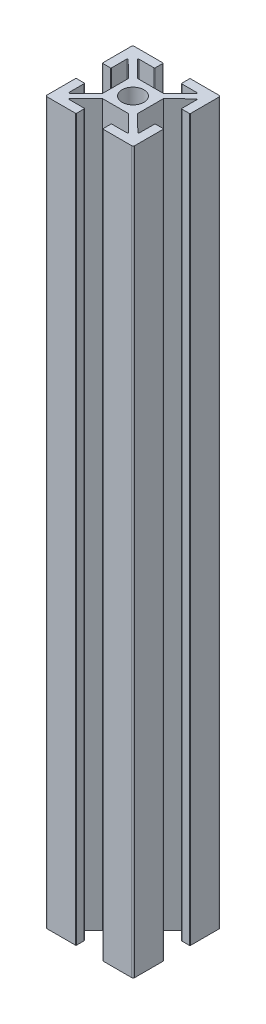
SolidWorks part; units mm, degrees
ref_plane "Front Plane" through (0, 0, 0) normal (0, 0, 1) x (1, 0, 0)
ref_plane "Top Plane" through (0, 0, 0) normal (0, 1, 0) x (1, 0, 0)
ref_plane "Right Plane" through (0, 0, 0) normal (1, 0, 0) x (0, 0, -1)
sketch "Sketch1" plane through (0, 0, 0) normal (0, 1, 0) x (1, 0, 0)
  line L0 (-9.8963, 3) -> (-8.1963, 3)
  line L3 (-3.1963, 10) -> (-9.6963, 10)
  line L4 (-10.0463, 3.15) -> (-10.0463, 9.65)
  line L7 (2.9332, 4) -> (-2.9332, 4)
  line L8 (-4, -2.9454) -> (-4, 2.9454)
  line L9 (-8.0463, 3.15) -> (-8.0463, 6.5862)
  line L10 (-6.6144, 8) -> (-3.1963, 8)
  line L11 (-3.0463, 8.15) -> (-3.0463, 9.85)
  line L12 (-8.0463, 8) -> (-4, 4) construction
  line L13 (-7.7908, 6.6929) -> (-4, 2.9454)
  line L14 (-6.7198, 7.7433) -> (-2.9332, 4)
  line L15 (8.0463, 8) -> (4, 4) construction
  line L22 (0, 0) -> (0, 11.6886) construction
  line L25 (0, 0) -> (-14.9841, 0) construction
  line L27 (6.7198, 7.7433) -> (2.9332, 4)
  line L28 (7.7908, 6.6929) -> (4, 2.9454)
  line L46 (3.0463, 8.15) -> (3.0463, 9.85)
  line L47 (6.6144, 8) -> (3.1963, 8)
  line L48 (8.0463, 3.15) -> (8.0463, 6.5862)
  line L49 (4, -2.9454) -> (4, 2.9454)
  line L50 (10.0463, 3.15) -> (10.0463, 9.65)
  line L51 (3.1963, 10) -> (9.6963, 10)
  line L52 (9.8963, 3) -> (8.1963, 3)
  line L53 (8.0463, -8) -> (4, -4) construction
  line L54 (-8.0463, -8) -> (-4, -4) construction
  line L55 (9.8963, -3) -> (8.1963, -3)
  line L56 (3.1963, -10) -> (9.6963, -10)
  line L57 (10.0463, -3.15) -> (10.0463, -9.65)
  line L58 (8.0463, -3.15) -> (8.0463, -6.5862)
  line L59 (6.6144, -8) -> (3.1963, -8)
  line L60 (3.0463, -8.15) -> (3.0463, -9.85)
  line L61 (7.7908, -6.6929) -> (4, -2.9454)
  line L62 (6.7198, -7.7433) -> (2.9332, -4)
  line L63 (-6.7198, -7.7433) -> (-2.9332, -4)
  line L64 (-7.7908, -6.6929) -> (-4, -2.9454)
  line L65 (-3.0463, -8.15) -> (-3.0463, -9.85)
  line L66 (-6.6144, -8) -> (-3.1963, -8)
  line L67 (-8.0463, -3.15) -> (-8.0463, -6.5862)
  line L68 (2.9332, -4) -> (-2.9332, -4)
  line L69 (-10.0463, -3.15) -> (-10.0463, -9.65)
  line L70 (-3.1963, -10) -> (-9.6963, -10)
  line L71 (-9.8963, -3) -> (-8.1963, -3)
  circle A0 centre (0, 0) radius 2.5
  arc A1 (-10.0463, 9.65) -> (-9.6963, 10) centre (-9.6963, 9.65) cw
  arc A2 (-9.8963, 3) -> (-10.0463, 3.15) centre (-9.8963, 3.15) cw
  arc A3 (-8.1963, 3) -> (-8.0463, 3.15) centre (-8.1963, 3.15) ccw
  arc A4 (-3.1963, 10) -> (-3.0463, 9.85) centre (-3.1963, 9.85) cw
  arc A5 (-3.1963, 8) -> (-3.0463, 8.15) centre (-3.1963, 8.15) ccw
  arc A6 (-6.7198, 7.7433) -> (-6.6144, 8) centre (-6.6144, 7.85) cw
  arc A7 (-7.7908, 6.6929) -> (-8.0463, 6.5862) centre (-7.8963, 6.5862) ccw
  arc A8 (7.7908, 6.6929) -> (8.0463, 6.5862) centre (7.8963, 6.5862) cw
  arc A9 (6.7198, 7.7433) -> (6.6144, 8) centre (6.6144, 7.85) ccw
  arc A10 (3.1963, 8) -> (3.0463, 8.15) centre (3.1963, 8.15) cw
  arc A11 (3.1963, 10) -> (3.0463, 9.85) centre (3.1963, 9.85) ccw
  arc A12 (8.1963, 3) -> (8.0463, 3.15) centre (8.1963, 3.15) cw
  arc A13 (9.8963, 3) -> (10.0463, 3.15) centre (9.8963, 3.15) ccw
  arc A14 (10.0463, 9.65) -> (9.6963, 10) centre (9.6963, 9.65) ccw
  arc A15 (10.0463, -9.65) -> (9.6963, -10) centre (9.6963, -9.65) cw
  arc A16 (9.8963, -3) -> (10.0463, -3.15) centre (9.8963, -3.15) cw
  arc A17 (8.1963, -3) -> (8.0463, -3.15) centre (8.1963, -3.15) ccw
  arc A18 (3.1963, -10) -> (3.0463, -9.85) centre (3.1963, -9.85) cw
  arc A19 (3.1963, -8) -> (3.0463, -8.15) centre (3.1963, -8.15) ccw
  arc A20 (6.7198, -7.7433) -> (6.6144, -8) centre (6.6144, -7.85) cw
  arc A21 (7.7908, -6.6929) -> (8.0463, -6.5862) centre (7.8963, -6.5862) ccw
  arc A22 (-7.7908, -6.6929) -> (-8.0463, -6.5862) centre (-7.8963, -6.5862) cw
  arc A23 (-6.7198, -7.7433) -> (-6.6144, -8) centre (-6.6144, -7.85) ccw
  arc A24 (-3.1963, -8) -> (-3.0463, -8.15) centre (-3.1963, -8.15) cw
  arc A25 (-3.1963, -10) -> (-3.0463, -9.85) centre (-3.1963, -9.85) ccw
  arc A26 (-8.1963, -3) -> (-8.0463, -3.15) centre (-8.1963, -3.15) cw
  arc A27 (-9.8963, -3) -> (-10.0463, -3.15) centre (-9.8963, -3.15) ccw
  arc A28 (-10.0463, -9.65) -> (-9.6963, -10) centre (-9.6963, -9.65) ccw
  point P8 (-10.0463, 10)
  point P27 (-10.0463, 3)
  point P30 (3.0463, 8)
  point P31 (10.0463, -10)
  point P50 (4, 0)
  point P55 (-8.0463, 3)
  point P58 (-3.0463, 10)
  point P61 (-3.0463, 8)
  point P63 (0, 4)
  point P65 (3.0463, 10)
  point P66 (8.0463, 3)
  point P67 (10.0463, 3)
  point P68 (10.0463, 10)
  point P118 (-4, 0)
  point P119 (10.0463, -3)
  point P120 (8.0463, -3)
  point P121 (3.0463, -10)
  point P122 (0, -4)
  point P123 (-3.0463, -8)
  point P124 (-3.0463, -10)
  point P125 (-8.0463, -3)
  point P126 (3.0463, -8)
  point P127 (-10.0463, -3)
  point P128 (-10.0463, -10)
  dimension "D2" = 0.35
  dimension "D3" = 0.15
  dimension "D4" = 0.15
  dimension "D5" = 0.15
  dimension "D12" = 0.15
  dimension "D13" = 0.15
  dimension "D14" = 0.15
  dimension "D6" = 2
  dimension "D7" = 7
  dimension "D8" = 7
  dimension "D9" = 2
  dimension "D10" = 0.75
  dimension "D11" = 0.75
extrude "Boss-Extrude2" add sketch "Sketch1" along normal blind 165
